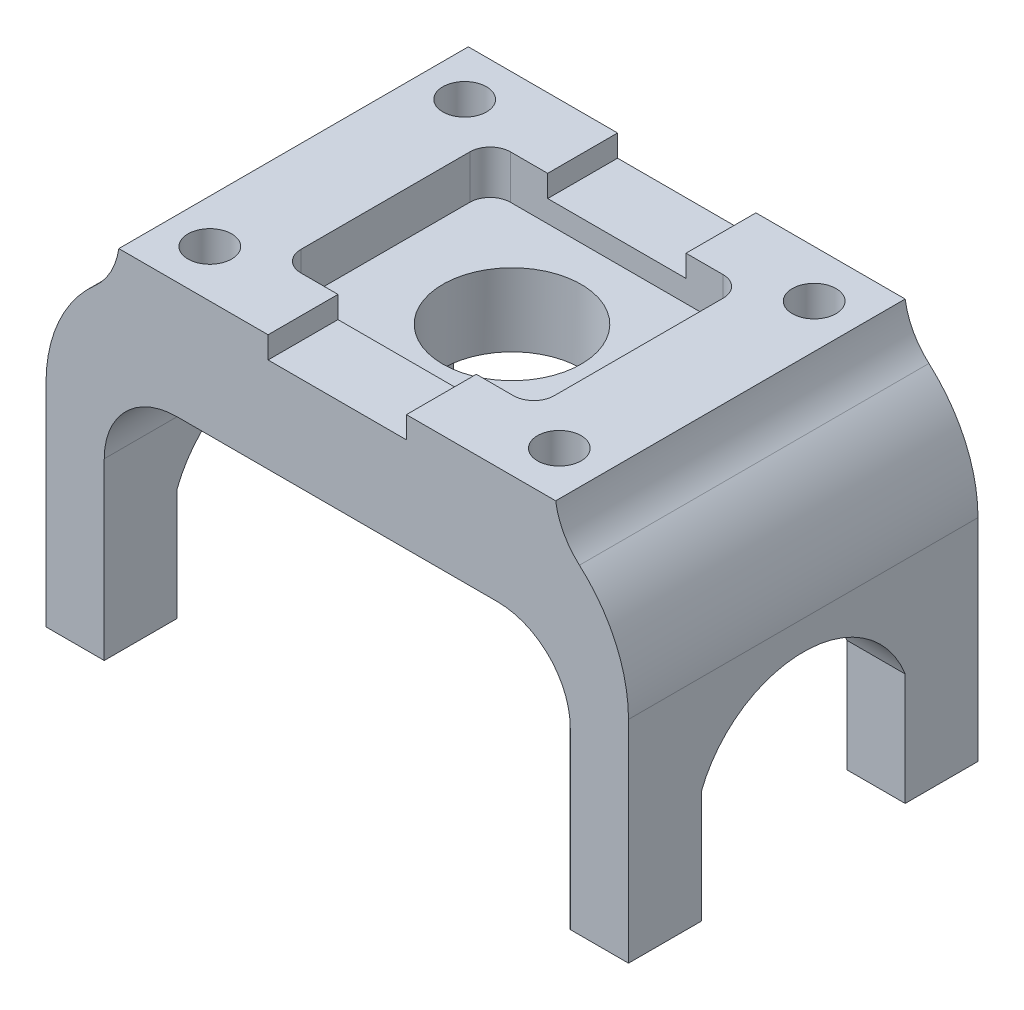
SolidWorks part; units mm, degrees
ref_plane "Front Plane" through (0, 0, 0) normal (0, 0, 1) x (1, 0, 0)
ref_plane "Top Plane" through (0, 0, 0) normal (0, 1, 0) x (1, 0, 0)
ref_plane "Right Plane" through (0, 0, 0) normal (1, 0, 0) x (0, 0, -1)
sketch "Sketch2" plane through (0, 0, 0) normal (0, 0, 1) x (1, 0, 0)
  line L0 (-35.383, -21.1492) -> (-35.383, 15.6808)
  line L1 (-35.383, -21.1492) -> (-25.223, -21.1492)
  line L2 (-25.223, -21.1492) -> (-25.223, 9.3308)
  line L3 (-12.523, 22.0308) -> (43.357, 22.0308)
  line L4 (15.417, 22.0308) -> (15.417, 38.5408) construction
  line L5 (27.482, 38.5408) -> (3.352, 38.5408)
  line L6 (3.352, 38.5408) -> (3.352, 42.3508)
  line L7 (3.352, 42.3508) -> (-22.683, 42.3508)
  line L8 (27.482, 42.3508) -> (53.517, 42.3508)
  line L9 (27.482, 38.5408) -> (27.482, 42.3508)
  line L10 (56.057, -21.1492) -> (56.057, 9.3308)
  line L11 (66.217, -21.1492) -> (56.057, -21.1492)
  line L12 (66.217, -21.1492) -> (66.217, 15.6808)
  arc A0 (-25.223, 9.3308) -> (-12.523, 22.0308) centre (-12.523, 9.3308) cw
  arc A1 (-35.383, 15.6808) -> (-26.8262, 34.6931) centre (-9.983, 15.6808) cw
  arc A2 (-26.8262, 34.6931) -> (-22.683, 42.3508) centre (-35.2477, 44.1993) ccw
  arc A3 (57.6602, 34.6931) -> (53.517, 42.3508) centre (66.0818, 44.1993) cw
  arc A4 (66.217, 15.6808) -> (57.6602, 34.6931) centre (40.817, 15.6808) ccw
  arc A5 (56.057, 9.3308) -> (43.357, 22.0308) centre (43.357, 9.3308) ccw
  point P11 (-14.3774, 40.6978)
  dimension "D4" = 12.7
  dimension "D6" = 63.5
  dimension "D7" = 3.81
  dimension "D8" = 25.4
  dimension "D9" = 12.7
  dimension "D1" = 36.83
  dimension "D2" = 10.16
  dimension "D3" = 30.48
  dimension "D5" = 40.64
  dimension "D10" = 12.065
  dimension "D11" = 76.2
extrude "Boss-Extrude1" add sketch "Sketch2" against normal blind 60.96 contours A1 A2 L7 L6 L5 L9 L8 A3 A4 L12 L11 L10 A5 L3 A0 L2 L1 L0
sketch "Sketch4" plane through (0, 38.5408, 0) normal (0, 1, 0) x (1, 0, 0)
  line L0 (3.352, 30.48) -> (15.417, 30.48) construction
  line L1 (-6.681, 48.768) -> (37.515, 48.768)
  line L2 (-6.681, 48.768) -> (-6.681, 12.192)
  line L3 (-6.681, 12.192) -> (37.515, 12.192)
  line L4 (37.515, 48.768) -> (37.515, 12.192)
  line L5 (-6.681, 48.768) -> (37.515, 12.192) construction
  line L6 (-6.681, 12.192) -> (37.515, 48.768) construction
  line L7 (3.352, 60.96) -> (3.352, 0) construction
  line L8 (15.417, 30.48) -> (15.417, 0) construction
  line L9 (27.482, 0) -> (3.352, 0) construction
  line L10 (53.517, 60.96) -> (53.517, 0) construction
  line L11 (-22.683, 60.96) -> (-22.683, 0) construction
  point P0 (15.417, 30.48)
  dimension "D1" = 16.002
  dimension "D2" = 12.192
  dimension "D3" = 16.002
extrude "Cut-Extrude1" cut sketch "Sketch4" against normal blind 3.81 and the other way blind 3.81
sketch "Sketch6" plane through (0, 42.3508, 0) normal (0, 1, 0) x (1, 0, 0)
  line L0 (-15.063, 52.705) -> (-15.063, 8.255) construction
  line L1 (-15.063, 8.255) -> (45.897, 8.255) construction
  line L2 (45.897, 8.255) -> (45.897, 52.705) construction
  line L3 (45.897, 52.705) -> (-15.063, 52.705) construction
  line L4 (53.517, 60.96) -> (53.517, 0) construction
  line L5 (3.352, 0) -> (-22.683, 0) construction
  line L8 (-15.063, 52.705) -> (45.897, 8.255) construction
  line L9 (45.897, 52.705) -> (-15.063, 8.255) construction
  circle A0 centre (15.417, 30.48) radius 12.065
  circle A1 centre (-15.063, 8.255) radius 3.81
  circle A2 centre (-15.063, 52.705) radius 3.81
  circle A3 centre (45.897, 52.705) radius 3.81
  circle A4 centre (45.897, 8.255) radius 3.81
  point P14 (15.417, 30.48)
  dimension "D1" = 24.13
  dimension "D2" = 60.96
  dimension "D3" = 7.62
  dimension "D4" = 8.255
  dimension "D5" = 44.45
  dimension "D6" = 7.62
  dimension "D7" = 7.62
  dimension "D8" = 7.62
  dimension "D9" = 7.62
extrude "Cut-Extrude2" cut sketch "Sketch6" against normal blind 40.64 contours A1
sketch "Sketch7" plane through (66.217, 0, 0) normal (1, 0, 0) x (0, 0, -1)
  line L0 (12.7, -21.1492) -> (12.7, -1.5912)
  line L1 (60.96, -21.1492) -> (0, -21.1492) construction
  line L2 (48.26, -21.1492) -> (48.26, -1.5912)
  line L3 (0, -21.1492) -> (0, 15.6808) construction
  line L4 (60.96, -21.1492) -> (60.96, 15.6808) construction
  line L5 (12.7, -1.5912) -> (48.26, -1.5912) construction
  arc A0 (12.7, -1.5912) -> (48.26, -1.5912) centre (30.48, -8.4303) cw
  dimension "D4" = 19.05
  dimension "D1" = 12.7
  dimension "D2" = 12.7
  dimension "D3" = 19.558
extrude "Cut-Extrude4" cut sketch "Sketch7" against normal through all and the other way through all contours L0 A0 L2
fillet "Fillet1" radius 3.556 4 edges at (37.515, 38.5408, -12.192) (37.515, 38.5408, -48.768) (-6.681, 38.5408, -12.192) (-6.681, 38.5408, -48.768)
